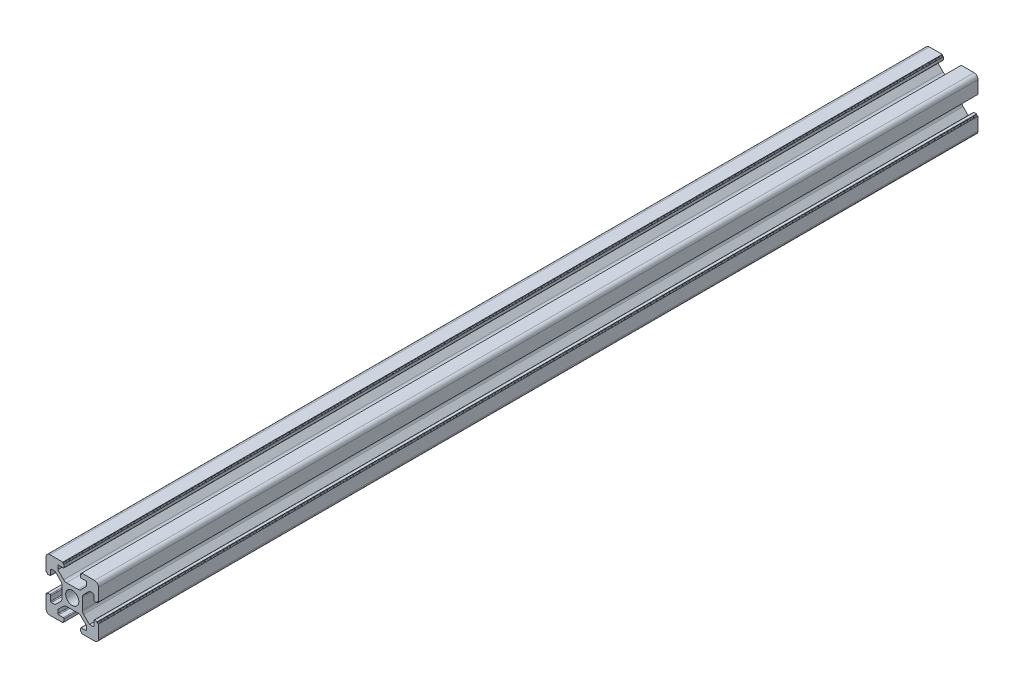
SolidWorks part; units mm, degrees
ref_plane "前视基准面" through (0, 0, 0) normal (0, 0, 1) x (1, 0, 0)
ref_plane "上视基准面" through (0, 0, 0) normal (0, 1, 0) x (1, 0, 0)
ref_plane "右视基准面" through (0, 0, 0) normal (1, 0, 0) x (0, 0, -1)
sketch "草图1" plane through (0, 0, 0) normal (0, 0, 1) x (1, 0, 0)
  line L0 (4.216, 3.2442) -> (6.4367, 5.4649)
  line L1 (6.4367, 5.4649) -> (7.7767, 5.4649)
  line L2 (8.0767, 5.1649) -> (8.0767, 3.3649)
  line L3 (8.3767, 3.0649) -> (9.3767, 3.0649)
  line L4 (9.3767, 3.0649) -> (9.3767, 3.3649)
  line L5 (9.5767, 3.5649) -> (9.8767, 3.5649)
  line L6 (9.8767, 3.5649) -> (9.8767, 8.4649)
  line L7 (8.3767, 9.9649) -> (3.4767, 9.9649)
  line L8 (3.4767, 9.9649) -> (3.4767, 9.6649)
  line L9 (3.2767, 9.4649) -> (2.9767, 9.4649)
  line L10 (2.9767, 9.4649) -> (2.9767, 8.4649)
  line L11 (3.2767, 8.1649) -> (5.0767, 8.1649)
  line L12 (5.3767, 7.8649) -> (5.3767, 6.5249)
  line L13 (5.3767, 6.5249) -> (3.156, 4.3042)
  line L14 (2.0953, 3.8649) -> (-2.342, 3.8649)
  line L15 (-3.4027, 4.3042) -> (-5.6233, 6.5249)
  line L16 (-5.6233, 6.5249) -> (-5.6233, 7.8649)
  line L17 (-5.3233, 8.1649) -> (-3.5233, 8.1649)
  line L18 (-3.2233, 8.4649) -> (-3.2233, 9.4649)
  line L19 (-3.2233, 9.4649) -> (-3.5233, 9.4649)
  line L20 (-3.7233, 9.6649) -> (-3.7233, 9.9649)
  line L21 (-3.7233, 9.9649) -> (-8.6233, 9.9649)
  line L22 (-10.1233, 8.4649) -> (-10.1233, 3.5649)
  line L23 (-10.1233, 3.5649) -> (-9.8233, 3.5649)
  line L24 (-9.6233, 3.3649) -> (-9.6233, 3.0649)
  line L25 (-9.6233, 3.0649) -> (-8.6233, 3.0649)
  line L26 (-8.3233, 3.3649) -> (-8.3233, 5.1649)
  line L27 (-8.0233, 5.4649) -> (-6.6833, 5.4649)
  line L28 (-6.6833, 5.4649) -> (-4.4627, 3.2442)
  line L29 (-4.0233, 2.1836) -> (-4.0233, -2.2538)
  line L30 (-4.4627, -3.3144) -> (-6.6833, -5.5351)
  line L31 (-6.6833, -5.5351) -> (-8.0233, -5.5351)
  line L32 (-8.3233, -5.2351) -> (-8.3233, -3.4351)
  line L33 (-8.6233, -3.1351) -> (-9.6233, -3.1351)
  line L34 (-9.6233, -3.1351) -> (-9.6233, -3.4351)
  line L35 (-9.8233, -3.6351) -> (-10.1233, -3.6351)
  line L36 (-10.1233, -3.6351) -> (-10.1233, -8.5351)
  line L37 (-8.6233, -10.0351) -> (-3.7233, -10.0351)
  line L38 (-3.7233, -10.0351) -> (-3.7233, -9.7351)
  line L39 (-3.5233, -9.5351) -> (-3.2233, -9.5351)
  line L40 (-3.2233, -9.5351) -> (-3.2233, -8.5351)
  line L41 (-3.5233, -8.2351) -> (-5.3233, -8.2351)
  line L42 (-5.6233, -7.9351) -> (-5.6233, -6.5951)
  line L43 (-5.6233, -6.5951) -> (-3.4027, -4.3744)
  line L44 (-2.342, -3.9351) -> (2.0953, -3.9351)
  line L45 (3.156, -4.3744) -> (5.3767, -6.5951)
  line L46 (5.3767, -6.5951) -> (5.3767, -7.9351)
  line L47 (5.0767, -8.2351) -> (3.2767, -8.2351)
  line L48 (2.9767, -8.5351) -> (2.9767, -9.5351)
  line L49 (2.9767, -9.5351) -> (3.2767, -9.5351)
  line L50 (3.4767, -9.7351) -> (3.4767, -10.0351)
  line L51 (3.4767, -10.0351) -> (8.3767, -10.0351)
  line L52 (9.8767, -8.5351) -> (9.8767, -3.6351)
  line L53 (9.8767, -3.6351) -> (9.5767, -3.6351)
  line L54 (9.3767, -3.4351) -> (9.3767, -3.1351)
  line L55 (9.3767, -3.1351) -> (8.3767, -3.1351)
  line L56 (8.0767, -3.4351) -> (8.0767, -5.2351)
  line L57 (7.7767, -5.5351) -> (6.4367, -5.5351)
  line L58 (6.4367, -5.5351) -> (4.216, -3.3144)
  line L59 (3.7767, -2.2538) -> (3.7767, 2.1836)
  circle A0 centre (-0.1233, -0.0351) radius 2.5
  arc A1 (8.0767, 5.1649) -> (7.7767, 5.4649) centre (7.7767, 5.1649) ccw
  arc A2 (8.0767, 3.3649) -> (8.3767, 3.0649) centre (8.3767, 3.3649) ccw
  arc A3 (9.5767, 3.5649) -> (9.3767, 3.3649) centre (9.5767, 3.3649) ccw
  arc A4 (9.8767, 8.4649) -> (8.3767, 9.9649) centre (8.3767, 8.4649) ccw
  arc A5 (3.2767, 9.4649) -> (3.4767, 9.6649) centre (3.2767, 9.6649) ccw
  arc A6 (2.9767, 8.4649) -> (3.2767, 8.1649) centre (3.2767, 8.4649) ccw
  arc A7 (5.3767, 7.8649) -> (5.0767, 8.1649) centre (5.0767, 7.8649) ccw
  arc A8 (2.0953, 3.8649) -> (3.156, 4.3042) centre (2.0953, 5.3649) ccw
  arc A9 (-3.4027, 4.3042) -> (-2.342, 3.8649) centre (-2.342, 5.3649) ccw
  arc A10 (-5.3233, 8.1649) -> (-5.6233, 7.8649) centre (-5.3233, 7.8649) ccw
  arc A11 (-3.5233, 8.1649) -> (-3.2233, 8.4649) centre (-3.5233, 8.4649) ccw
  arc A12 (-3.7233, 9.6649) -> (-3.5233, 9.4649) centre (-3.5233, 9.6649) ccw
  arc A13 (-8.6233, 9.9649) -> (-10.1233, 8.4649) centre (-8.6233, 8.4649) ccw
  arc A14 (-9.6233, 3.3649) -> (-9.8233, 3.5649) centre (-9.8233, 3.3649) ccw
  arc A15 (-8.6233, 3.0649) -> (-8.3233, 3.3649) centre (-8.6233, 3.3649) ccw
  arc A16 (-8.0233, 5.4649) -> (-8.3233, 5.1649) centre (-8.0233, 5.1649) ccw
  arc A17 (-4.0233, 2.1836) -> (-4.4627, 3.2442) centre (-5.5233, 2.1836) ccw
  arc A18 (-4.4627, -3.3144) -> (-4.0233, -2.2538) centre (-5.5233, -2.2538) ccw
  arc A19 (-8.3233, -5.2351) -> (-8.0233, -5.5351) centre (-8.0233, -5.2351) ccw
  arc A20 (-8.3233, -3.4351) -> (-8.6233, -3.1351) centre (-8.6233, -3.4351) ccw
  arc A21 (-9.8233, -3.6351) -> (-9.6233, -3.4351) centre (-9.8233, -3.4351) ccw
  arc A22 (-10.1233, -8.5351) -> (-8.6233, -10.0351) centre (-8.6233, -8.5351) ccw
  arc A23 (-3.5233, -9.5351) -> (-3.7233, -9.7351) centre (-3.5233, -9.7351) ccw
  arc A24 (-3.2233, -8.5351) -> (-3.5233, -8.2351) centre (-3.5233, -8.5351) ccw
  arc A25 (-5.6233, -7.9351) -> (-5.3233, -8.2351) centre (-5.3233, -7.9351) ccw
  arc A26 (-2.342, -3.9351) -> (-3.4027, -4.3744) centre (-2.342, -5.4351) ccw
  arc A27 (3.156, -4.3744) -> (2.0953, -3.9351) centre (2.0953, -5.4351) ccw
  arc A28 (5.0767, -8.2351) -> (5.3767, -7.9351) centre (5.0767, -7.9351) ccw
  arc A29 (3.2767, -8.2351) -> (2.9767, -8.5351) centre (3.2767, -8.5351) ccw
  arc A30 (3.4767, -9.7351) -> (3.2767, -9.5351) centre (3.2767, -9.7351) ccw
  arc A31 (8.3767, -10.0351) -> (9.8767, -8.5351) centre (8.3767, -8.5351) ccw
  arc A32 (9.3767, -3.4351) -> (9.5767, -3.6351) centre (9.5767, -3.4351) ccw
  arc A33 (8.3767, -3.1351) -> (8.0767, -3.4351) centre (8.3767, -3.4351) ccw
  arc A34 (7.7767, -5.5351) -> (8.0767, -5.2351) centre (7.7767, -5.2351) ccw
  arc A35 (3.7767, -2.2538) -> (4.216, -3.3144) centre (5.2767, -2.2538) ccw
  arc A36 (4.216, 3.2442) -> (3.7767, 2.1836) centre (5.2767, 2.1836) ccw
extrude "凸台-拉伸1" add sketch "草图1" along normal blind 335
